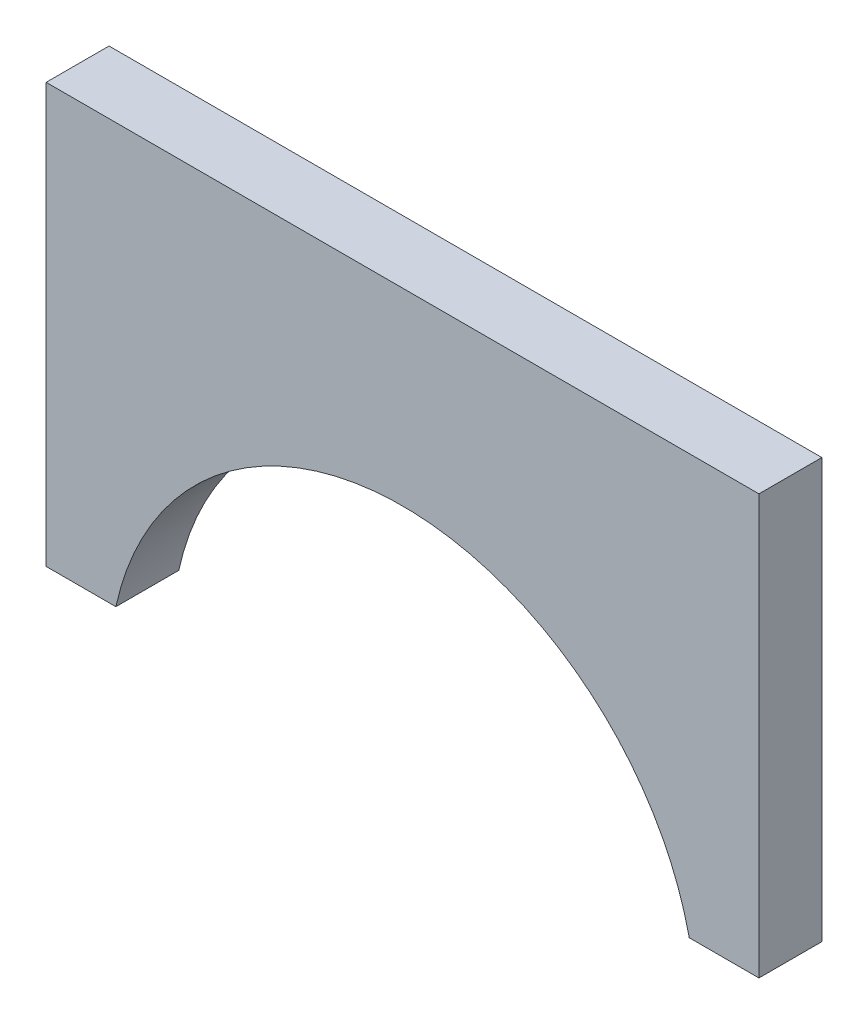
SolidWorks part; units mm, degrees
ref_plane "Front Plane" through (0, 0, 0) normal (0, 0, 1) x (1, 0, 0)
ref_plane "Top Plane" through (0, 0, 0) normal (0, 1, 0) x (1, 0, 0)
ref_plane "Right Plane" through (0, 0, 0) normal (1, 0, 0) x (0, 0, -1)
sketch "Sketch1" plane through (0, 0, 0) normal (0, 0, 1) x (1, 0, 0)
  line L0 (13.6748, -10) -> (17, -10)
  line L1 (-17, -10) -> (-13.6748, -10)
  line L2 (-17, -10) -> (-17, 10)
  line L3 (-17, 10) -> (17, 10)
  line L4 (17, -10) -> (17, 10)
  line L5 (-17, -10) -> (17, 10) construction
  line L6 (-17, 10) -> (17, -10) construction
  arc A0 (13.6748, -10) -> (-13.6748, -10) centre (0, -13) ccw
  point P0 (0, 0)
  dimension "D3" = 28
  dimension "D1" = 34
  dimension "D2" = 20
  dimension "D4" = 3
extrude "Boss-Extrude1" add sketch "Sketch1" along normal blind 3
